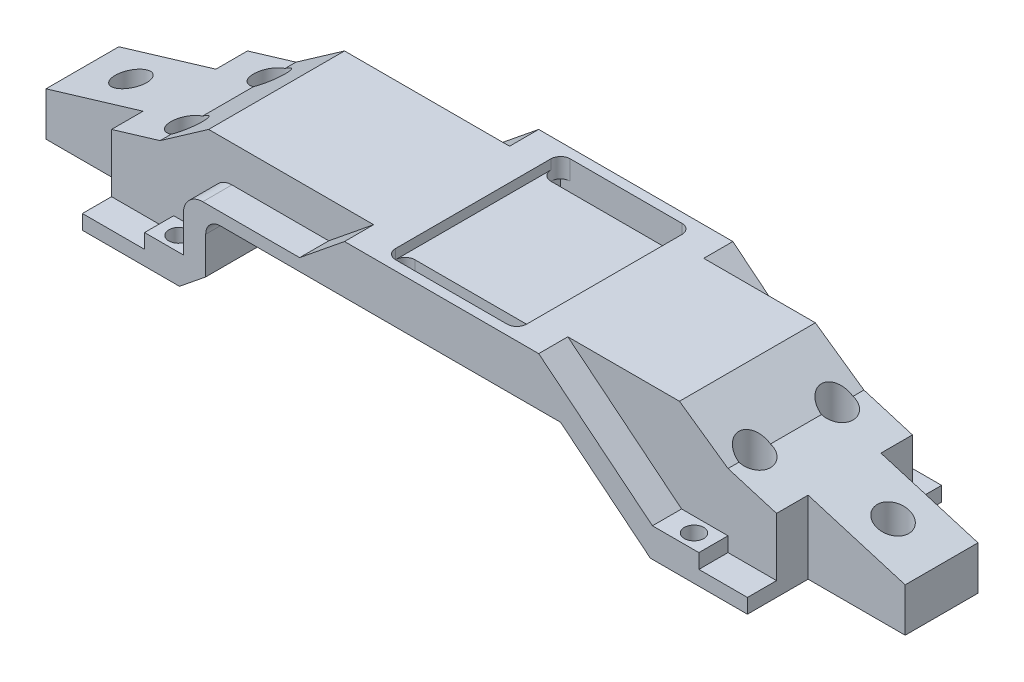
SolidWorks part; units mm, degrees
ref_plane "Front Plane" through (0, 0, 0) normal (0, 0, 1) x (1, 0, 0)
ref_plane "Top Plane" through (0, 0, 0) normal (0, 1, 0) x (1, 0, 0)
ref_plane "Right Plane" through (0, 0, 0) normal (1, 0, 0) x (0, 0, -1)
sketch "Sketch1" plane through (0, 0, 0) normal (0, 1, 0) x (1, 0, 0)
  line L0 (68.5, 20) -> (68.5, 7.5)
  line L1 (-68.5, 20) -> (68.5, 20)
  line L3 (-68.5, -20) -> (68.5, -20)
  line L5 (-68.5, 20) -> (68.5, -20) construction
  line L6 (-68.5, -20) -> (68.5, 20) construction
  line L7 (68.5, 7.5) -> (88.5, 7.5)
  line L8 (88.5, 7.5) -> (88.5, -7.5)
  line L9 (88.5, -7.5) -> (68.5, -7.5)
  line L10 (68.5, -7.5) -> (68.5, -20)
  line L11 (0, 0) -> (0, -116.996) construction
  line L12 (-68.5, -7.5) -> (-68.5, -20)
  line L13 (-88.5, -7.5) -> (-68.5, -7.5)
  line L14 (-88.5, 7.5) -> (-88.5, -7.5)
  line L15 (-68.5, 7.5) -> (-88.5, 7.5)
  line L16 (-68.5, 20) -> (-68.5, 7.5)
  circle A0 centre (-78.5, 0) radius 1.8
  circle A1 centre (-58.5, 8.5) radius 1.8
  circle A2 centre (-58.5, -8.5) radius 1.8
  circle A3 centre (58.5, -8.5) radius 1.8
  circle A4 centre (78.5, 0) radius 1.8
  circle A5 centre (58.5, 8.5) radius 1.8
  point P0 (0, 0)
  dimension "D6" = 3.6
  dimension "D1" = 137
  dimension "D2" = 40
  dimension "D3" = 20
  dimension "D4" = 15
  dimension "D5" = 12.5
  dimension "D7" = 7.5
  dimension "D8" = 10
  dimension "D9" = 10
  dimension "D10" = 1
  dimension "D11" = 10
  dimension "D12" = 1
extrude "Boss-Extrude1" add sketch "Sketch1" along normal blind 6
sketch "Sketch2" plane through (0, 0, -20) normal (0, 0, -1) x (-1, 0, 0)
  line L1 (-68.5, 6) -> (68.5, 6) construction
  line L4 (-88.5, 6) -> (-68.5, 6) construction
  line L5 (-88.5, 6) -> (88.5, 6)
  line L7 (-58.5, 18) -> (-88.5, 9)
  line L8 (-88.5, 9) -> (-88.5, 6)
  line L9 (-88.5, 6) -> (-88.5, 0) construction
  line L10 (58.5, 18) -> (88.5, 9)
  line L11 (88.5, 9) -> (88.5, 6)
  line L12 (88.5, 6) -> (88.5, 0) construction
  line L13 (58.5, 18) -> (48.5, 25)
  line L14 (48.5, 25) -> (-48.5, 25)
  line L15 (-48.5, 25) -> (-58.5, 18)
  point P12 (0, 0)
  dimension "D5" = 3
  dimension "D1" = 3
  dimension "D3" = 30
  dimension "D4" = 30
  dimension "D2" = 12
  dimension "D8" = 10
  dimension "D9" = 10
  dimension "D6" = 12
  dimension "D7" = 7
extrude "Boss-Extrude2" add sketch "Sketch2" against normal up to surface (40 mm away) up to face at (0, 3, 20)
sketch "Sketch3" plane through (0, 6, 0) normal (0, -1, 0) x (1, 0, 0)
  line L16 (88.5, 20) -> (88.5, 7.5) construction
  line L21 (-88.5, 20) -> (-68.5, 20)
  line L22 (-88.5, 20) -> (-88.5, 7.5)
  line L23 (-88.5, 7.5) -> (-68.5, 7.5)
  line L24 (-68.5, 20) -> (-68.5, 7.5)
  line L25 (-68.5, -7.5) -> (-88.5, -7.5)
  line L26 (-68.5, -7.5) -> (-68.5, -20)
  line L27 (-68.5, -20) -> (-88.5, -20)
  line L28 (-88.5, -7.5) -> (-88.5, -20)
  line L29 (68.5, 7.5) -> (88.5, 7.5)
  line L30 (68.5, 7.5) -> (68.5, 20)
  line L31 (68.5, 20) -> (88.5, 20)
  line L32 (88.5, 7.5) -> (88.5, 20)
  line L33 (68.5, -7.5) -> (88.5, -7.5)
  line L34 (68.5, -7.5) -> (68.5, -20)
  line L35 (68.5, -20) -> (88.5, -20)
  line L36 (88.5, -7.5) -> (88.5, -20)
extrude "Cut-Extrude1" cut sketch "Sketch3" against normal up to next
sketch "Sketch4" plane through (0, 25, 0) normal (0, 1, 0) x (1, 0, 0)
  circle A0 centre (-58.5, 8.5) radius 3.25
  circle A1 centre (-78.5, 0) radius 3.25
  circle A2 centre (-58.5, -8.5) radius 3.25
  circle A3 centre (58.5, 8.5) radius 3.25
  circle A4 centre (58.5, -8.5) radius 3.25
  circle A5 centre (78.5, 0) radius 3.25
  dimension "D1" = 6.5
extrude "Cut-Extrude2" cut sketch "Sketch4" against normal up to surface (19 mm away) up to face at (-78.5, 6, 1.8)
sketch "Sketch5" plane through (0, 0, -20) normal (0, 0, -1) x (-1, 0, 0)
  line L0 (48.5, 0) -> (30, 15)
  line L1 (-68.5, 0) -> (68.5, 0) construction
  line L2 (30, 15) -> (-30, 15)
  line L3 (-30, 15) -> (-48.5, 0)
  line L6 (-48.5, 0) -> (48.5, 0)
  point P2 (0, 0)
  point P3 (0, 0)
  dimension "D1" = 15
  dimension "D2" = 97
  dimension "D3" = 20
  dimension "D4" = 60
  dimension "D5" = 18.5
extrude "Cut-Extrude3" cut sketch "Sketch5" against normal up to next
sketch "Sketch6" plane through (0, 0, -20) normal (0, 0, -1) x (-1, 0, 0)
  line L0 (43.1, 4.3784) -> (43.1, 20.3784)
  line L1 (48.5, 0) -> (30, 15) construction
  line L2 (43.1, 20.3784) -> (-53.9, 20.3784)
  line L3 (-53.9, 20.3784) -> (-53.9, 0)
  line L4 (-68.5, 0) -> (-48.5, 0) construction
  line L6 (43.1, 4.3784) -> (30, 15)
  line L7 (30, 15) -> (-30, 15)
  line L8 (-30, 15) -> (-48.5, 0)
  line L9 (-48.5, 0) -> (-53.9, 0)
  point P14 (0, 0)
  dimension "D1" = 97
  dimension "D2" = 16
  dimension "D3" = 5.4
extrude "Cut-Extrude4" cut sketch "Sketch6" against normal blind 26 from offset 7 offset against normal yes
sketch "Sketch7" plane through (0, 15, 0) normal (0, -1, 0) x (-1, 0, 0)
  line L0 (30, -20) -> (30, -13) construction
  line L1 (8, -18) -> (-19, -18)
  line L2 (8, -18) -> (8, 18)
  line L3 (8, 18) -> (-19, 18)
  line L4 (-19, -18) -> (-19, 18)
  line L5 (-30, -20) -> (30, -20) construction
  dimension "D1" = 36
  dimension "D2" = 27
  dimension "D3" = 22
  dimension "D4" = 2
extrude "Cut-Extrude5" cut sketch "Sketch7" against normal blind 6
sketch "Sketch8" plane through (0, 21, 0) normal (0, -1, 0) x (1, 0, 0)
  line L0 (17, -16) -> (-6, -16) construction
  line L1 (17, -18) -> (-6, -18)
  line L2 (17, -14) -> (-6, -14)
  line L3 (-8, -13) -> (-8, -18) construction
  line L4 (-8, -18) -> (19, -18) construction
  line L5 (17, 16) -> (-6, 16) construction
  line L6 (17, 14) -> (-6, 14)
  line L7 (17, 18) -> (-6, 18)
  line L8 (-8, 18) -> (-8, 13) construction
  line L9 (19, 18) -> (-8, 18) construction
  arc A0 (17, -18) -> (17, -14) centre (17, -16) ccw
  arc A1 (-6, -14) -> (-6, -18) centre (-6, -16) ccw
  arc A2 (17, 14) -> (17, 18) centre (17, 16) ccw
  arc A3 (-6, 18) -> (-6, 14) centre (-6, 16) ccw
  point P2 (5.5, -16)
  point P13 (5.5, 16)
  dimension "D1" = 2
  dimension "D5" = 2
  dimension "D2" = 23
  dimension "D3" = 2
  dimension "D4" = 2
  dimension "D6" = 23
  dimension "D7" = 2
  dimension "D8" = 2
extrude "Cut-Extrude6" cut sketch "Sketch8" against normal up to next
sketch "Sketch9" plane through (0, 25, 0) normal (0, 1, 0) x (1, 0, 0)
  line L1 (19, -16) -> (-8, -16)
  line L2 (19, -16) -> (19, 16)
  line L3 (19, 16) -> (-8, 16)
  line L4 (-8, -16) -> (-8, 16)
  arc A0 (17, -18) -> (17, -14) centre (17, -16) ccw construction
  arc A1 (-6, 18) -> (-6, 14) centre (-6, 16) ccw construction
extrude "Cut-Extrude7" cut sketch "Sketch9" against normal blind 2
sketch "Sketch10" plane through (0, 0, -20) normal (0, 0, -1) x (-1, 0, 0)
  line L6 (43.1, 4.3784) -> (30, 15)
  line L7 (48.5, 0) -> (30, 15) construction
  line L9 (43.1, 4.3784) -> (43.1, 15)
  line L10 (43.1, 15) -> (30, 15)
extrude "Cut-Extrude10" cut sketch "Sketch10" against normal through all
fillet "Fillet1" radius 3 2 edges at (-43.1, 15, -16.5) (-43.1, 15, 16.5)
sketch "Sketch11" plane through (0, 0, 20) normal (0, 0, 1) x (1, 0, 0)
  line L0 (25.5, 25) -> (48.5, 25)
  line L1 (48.5, 25) -> (-48.5, 25) construction
  line L2 (58.5, 18) -> (48.5, 25) construction
  line L3 (48.5, 25) -> (58.5, 18)
  line L4 (58.5, 18) -> (68.5, 15)
  line L5 (68.5, 15) -> (68.5, 3)
  line L6 (68.5, 15) -> (68.5, 0) construction
  line L7 (68.5, 3) -> (52.6333, 3)
  line L8 (52.6333, 3) -> (25.5, 25)
  line L9 (48.5, 0) -> (30, 15) construction
  line L10 (0, 23.0743) -> (0, 7) construction
  line L12 (-68.5, 3) -> (-47.7, 3)
  line L13 (-68.5, 15) -> (-68.5, 3)
  line L14 (-58.5, 18) -> (-68.5, 15)
  line L15 (-48.5, 25) -> (-58.5, 18)
  line L16 (-14.5, 25) -> (-48.5, 25)
  line L17 (-47.7, 3) -> (-47.7, 13.5)
  line L18 (-14.5, 25) -> (-23.75, 17.5)
  line L20 (-23.75, 17.5) -> (-43.7, 17.5)
  line L22 (-43.1, 4.3784) -> (-43.1, 12) construction
  line L23 (30, 15) -> (-40.1, 15) construction
  arc A0 (-47.7, 13.5) -> (-43.7, 17.5) centre (-43.7, 13.5) cw
  point P32 (-14.3791, 21.8924)
  point P33 (0, 0)
  dimension "D7" = 4
  dimension "D1" = 23
  dimension "D2" = 12
  dimension "D3" = 48.5
  dimension "D4" = 4.6
  dimension "D5" = 39.036
  dimension "D6" = 2.5
  dimension "D8" = 40
extrude "Cut-Extrude11" cut sketch "Sketch11" against normal blind 6
ref_plane "Plane2" through (0, 0, 0) normal (0, 0, -1) x (-1, 0, 0)
mirror "Mirror1" about plane through (0, 0, 0) normal (0, 0, -1) of "Cut-Extrude11"
sketch "Sketch12" plane through (0, 3, 0) normal (0, 1, 0) x (1, 0, 0)
  line L0 (-68.5, 20) -> (-47.7, 20) construction
  line L1 (-47.7, 14) -> (-55.7, 14)
  line L2 (-47.7, 14) -> (-47.7, 20)
  line L3 (-47.7, 20) -> (-55.7, 20)
  line L4 (-55.7, 14) -> (-55.7, 20)
  line L5 (-48.5, -14) -> (-58.5, -14) construction
  line L6 (-47.7, -20) -> (-55.7, -20)
  line L7 (-47.7, -20) -> (-47.7, -14)
  line L8 (-47.7, -14) -> (-55.7, -14)
  line L9 (-55.7, -20) -> (-55.7, -14)
  line L10 (52.6333, -20) -> (68.5, -20) construction
  line L11 (58.5, -20) -> (48.5, -20)
  line L12 (58.5, -20) -> (58.5, -14)
  line L13 (58.5, -14) -> (48.5, -14)
  line L14 (48.5, -20) -> (48.5, -14)
  line L15 (52.6333, 20) -> (68.5, 20) construction
  line L16 (58.5, 20) -> (48.5, 20)
  line L17 (58.5, 20) -> (58.5, 14)
  line L18 (58.5, 14) -> (48.5, 14)
  line L19 (48.5, 20) -> (48.5, 14)
  line L20 (68.5, -14) -> (58.5, -14) construction
  line L21 (68.5, 14) -> (58.5, 14) construction
  line L22 (68.5, 14) -> (68.5, 20) construction
  dimension "D1" = 8
  dimension "D2" = 10
  dimension "D3" = 10
extrude "Boss-Extrude3" add sketch "Sketch12" along normal blind 3
sketch "Sketch13" plane through (0, 6, 0) normal (0, 1, 0) x (1, 0, 0)
  line L0 (58.5, -20) -> (58.5, -14) construction
  line L1 (48.9333, -20) -> (58.5, -20) construction
  line L3 (-55.7, -14) -> (-55.7, -20) construction
  line L4 (58.5, 20) -> (48.9333, 20) construction
  circle A0 centre (54.5, -17) radius 2
  circle A1 centre (54.5, 17) radius 2
  circle A2 centre (-51.7, 17) radius 2
  circle A3 centre (-51.7, -17) radius 2
  point P8 (0, 0)
  point P9 (0, 0)
  point P10 (0, 0)
  point P11 (0, 0)
  point P16 (54.5, 17.4832)
  dimension "D1" = 4
  dimension "D2" = 4
  dimension "D3" = 3
  dimension "D4" = 3
  dimension "D5" = 4
extrude "Cut-Extrude12" cut sketch "Sketch13" against normal blind 6
equation "\"D5@Sketch1\"=(\"D2@Sketch1\"-\"D4@Sketch1\")/2"
equation "\"D4@Sketch2\"=\"D3@Sketch2\""
equation "\"D6@Sketch2\"=\"D2@Sketch2\""
equation "\"D5@Sketch5\"=(\"D2@Sketch5\"-\"D4@Sketch5\")/2"
equation "\"D4@Sketch7\"=(40-\"D1@Sketch7\")/2"
